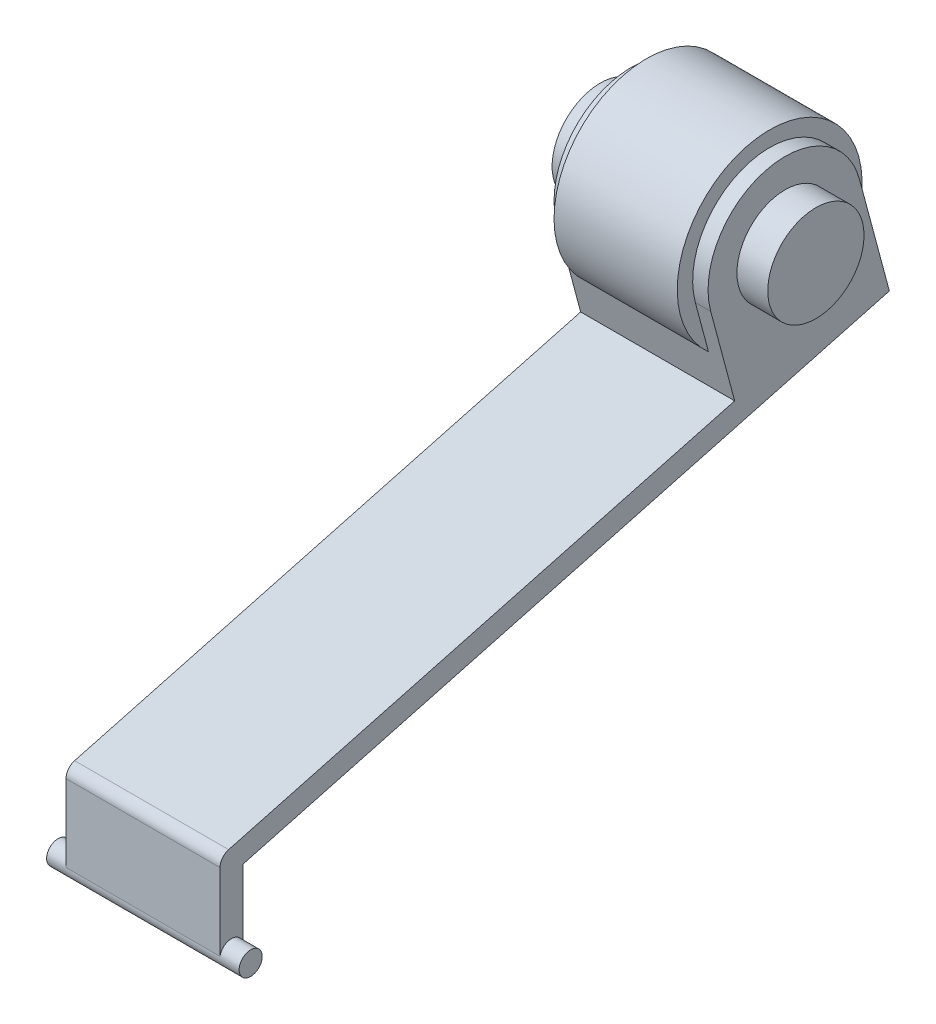
SolidWorks part; units mm, degrees
ref_plane "Front Plane" through (0, 0, 0) normal (0, 0, 1) x (1, 0, 0)
ref_plane "Top Plane" through (0, 0, 0) normal (0, 1, 0) x (1, 0, 0)
ref_plane "Right Plane" through (0, 0, 0) normal (1, 0, 0) x (0, 0, -1)
sketch "Sketch1" plane through (0, 0, 0) normal (1, 0, 0) x (0, 0, -1)
  circle A0 centre (0, 0) radius 0.3
extrude "Boss-Extrude1" add sketch "Sketch1" along normal mid plane 5
sketch "Sketch2" plane through (0, 0, 0) normal (1, 0, 0) x (0, 0, -1)
  line L0 (-0.2962, 0.0475) -> (-0.2962, 2.0475)
  line L1 (-0.0726, 2.3389) -> (15, 6.3776)
  line L2 (15, 6.3776) -> (15.1533, 5.8054)
  line L4 (0.2962, 1.8244) -> (0.2962, 0.0475)
  line L5 (0.2962, 0.0475) -> (-0.2962, 0.0475)
  line L6 (0.2962, 1.8244) -> (15.1533, 5.8054)
  circle A0 centre (0, 0) radius 0.3 construction
  arc A1 (-0.2962, 2.0475) -> (-0.0726, 2.3389) centre (0.0055, 2.0475) cw
  dimension "D1" = 75
  dimension "D2" = 15
  dimension "D3" = 2
extrude "Boss-Extrude2" add sketch "Sketch2" along normal blind 2 and the other way blind 2
sketch "Sketch4" plane through (2, 0, 0) normal (1, 0, 0) x (0, 0, -1)
  line L0 (13.2215, 5.2878) -> (17.0852, 6.323)
  line L2 (0.2962, 1.8244) -> (15.1533, 5.8054) construction
  line L3 (17.0852, 6.323) -> (16.3087, 9.2208)
  line L4 (12.445, 8.1855) -> (13.2215, 5.2878)
  line L5 (15.1533, 5.8054) -> (15, 6.3776) construction
  arc A0 (16.3087, 9.2208) -> (12.445, 8.1855) centre (14.3769, 8.7032) ccw
  point P9 (13.8592, 10.635)
  dimension "D1" = 2
  dimension "D2" = 4
  dimension "D3" = 5
extrude "Boss-Extrude3" add sketch "Sketch4" against normal blind 4
sketch "Sketch5" plane through (0, 0, 0) normal (1, 0, 0) x (0, 0, -1)
  circle A0 centre (14.3769, 8.7032) radius 2.4
  dimension "D1" = 4.8
extrude "Boss-Extrude4" add sketch "Sketch5" along normal blind 1.6 and the other way blind 1.6
sketch "Sketch6" plane through (0, 0, 0) normal (1, 0, 0) x (0, 0, -1)
  circle A0 centre (14.3769, 8.7032) radius 1.25
  dimension "D1" = 2.5
extrude "Boss-Extrude5" add sketch "Sketch6" along normal blind 2.8 and the other way blind 2.8
